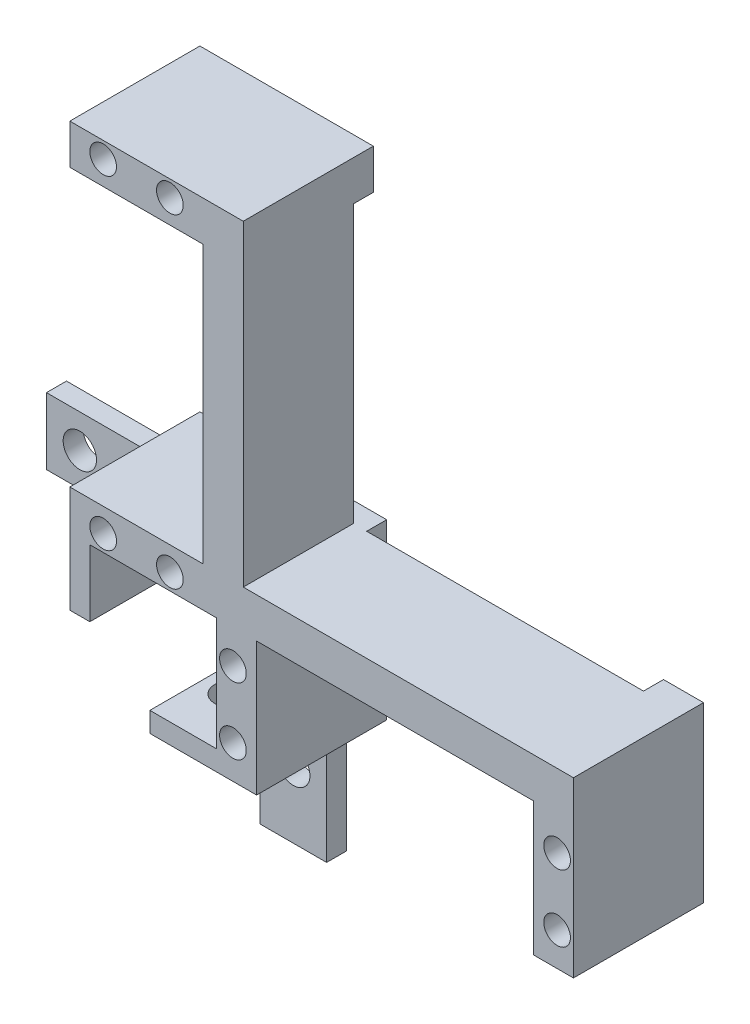
SolidWorks part; units mm, degrees
ref_plane "前视基准面" through (0, 0, 0) normal (0, 0, 1) x (1, 0, 0)
ref_plane "上视基准面" through (0, 0, 0) normal (0, 1, 0) x (1, 0, 0)
ref_plane "右视基准面" through (0, 0, 0) normal (1, 0, 0) x (0, 0, -1)
sketch "草图1" plane through (0, 0, 0) normal (0, 0, 1) x (1, 0, 0)
  line L0 (0, 38.2514) -> (0, 0) construction
  line L1 (0, 0) -> (26.75, 0)
  line L2 (26.75, 0) -> (26.75, -20)
  line L3 (26.75, -20) -> (36.75, -20)
  line L4 (0, -6) -> (20.75, -6)
  line L5 (20.75, -6) -> (20.75, -26)
  line L6 (20.75, -26) -> (36.75, -26)
  line L7 (-36.75, -20) -> (-36.75, -26)
  line L8 (36.75, -20) -> (36.75, -26)
  line L9 (-20.75, -26) -> (-36.75, -26)
  line L10 (-20.75, -6) -> (-20.75, -26)
  line L11 (0, -6) -> (-20.75, -6)
  line L12 (-26.75, -20) -> (-36.75, -20)
  line L13 (-26.75, 0) -> (-26.75, -20)
  line L14 (0, 0) -> (-26.75, 0)
  dimension "D2" = 41.5
  dimension "D3" = 20
  dimension "D4" = 10
  dimension "D5" = 0
  dimension "D1" = 6
extrude "凸台-拉伸1" add sketch "草图1" along normal blind 16.5
sketch "草图2" plane through (0, -20, 0) normal (0, 1, 0) x (1, 0, 0)
  line L0 (36.75, -16.5) -> (26.75, -16.5) construction
  line L1 (36.75, -16.5) -> (36.75, 0) construction
  circle A0 centre (32.75, -8.25) radius 2.5
  dimension "D1" = 5
  dimension "D2" = 8.25
  dimension "D3" = 4
extrude "切除-拉伸1" cut sketch "草图2" against normal blind 16.5
sketch "草图3" plane through (0, -20, 0) normal (0, 1, 0) x (1, 0, 0)
  line L1 (36.75, 0) -> (26.75, 0)
  line L2 (36.75, 0) -> (36.75, -16.5)
  line L3 (36.75, -16.5) -> (26.75, -16.5)
  line L4 (26.75, 0) -> (26.75, -16.5)
extrude "切除-拉伸2" cut sketch "草图3" against normal blind 3
sketch "草图4" plane through (0, 0, 16.5) normal (0, 0, 1) x (1, 0, 0)
  line L2 (-26.75, 0) -> (-38.6463, 0)
  line L3 (-26.75, 0) -> (-26.75, -29.0846)
  line L4 (-26.75, -29.0846) -> (-38.6463, -29.0846)
  line L5 (-38.6463, 0) -> (-38.6463, -29.0846)
extrude "切除-拉伸3" cut sketch "草图4" against normal through all
sketch "草图5" plane through (0, 0, 0) normal (0, 0, -1) x (-1, 0, 0)
  line L0 (20.75, -16) -> (-20.75, -16) construction
  line L1 (20.75, -26) -> (20.75, -6) construction
  line L2 (-20.75, -6) -> (-20.75, -26) construction
  line L3 (0, 0) -> (0, -37.9358) construction
  line L4 (-26.75, 0) -> (26.75, 0) construction
  circle A0 centre (-24.3, -11) radius 2
  circle A1 centre (-24.3, -21) radius 2
  circle A2 centre (24.3, -21) radius 2
  circle A3 centre (24.3, -11) radius 2
  dimension "D1" = 4
  dimension "D2" = 4
  dimension "D3" = 10
  dimension "D4" = 5
  dimension "D5" = 24.3
  dimension "D6" = 24.3
extrude "切除-拉伸4" cut sketch "草图5" against normal through all
sketch "草图6" plane through (0, 0, 0) normal (0, 0, -1) x (-1, 0, 0)
  line L1 (-26.75, -23) -> (-36.75, -23)
  line L2 (-26.75, -23) -> (-26.75, -46)
  line L3 (-26.75, -46) -> (-36.75, -46)
  line L4 (-36.75, -23) -> (-36.75, -46)
  dimension "D1" = 23
extrude "凸台-拉伸2" add sketch "草图6" along normal blind 3
sketch "草图7" plane through (0, 0, -3) normal (0, 0, -1) x (-1, 0, 0)
  line L0 (-36.75, -46) -> (-26.75, -46) construction
  line L1 (-36.75, -23) -> (-36.75, -46) construction
  circle A0 centre (-31.75, -36) radius 2.5
  dimension "D1" = 5
  dimension "D2" = 10
  dimension "D3" = 5
extrude "切除-拉伸5" cut sketch "草图7" against normal blind 3
sketch "草图8" plane through (0, 0, 0) normal (0, 0, -1) x (-1, 0, 0)
  line L0 (-36.75, -46) -> (-26.75, -46) construction
  line L1 (26.75, 0) -> (20.75, 0)
  line L2 (26.75, 0) -> (26.75, -26)
  line L3 (26.75, -46) -> (20.75, -46)
  line L4 (20.75, 0) -> (20.75, -46)
  line L6 (26.75, -46) -> (30.75, -46)
  line L8 (26.75, -26) -> (30.75, -26)
  line L9 (30.75, -46) -> (30.75, -26)
  line L11 (-20.75, -26) -> (-26.75, -26)
  line L12 (-20.75, -26) -> (-20.75, 0)
  line L13 (-20.75, 0) -> (-26.75, 0)
  line L14 (-26.75, -26) -> (-26.75, 0)
  circle A0 centre (24.3, -21) radius 2 construction
  circle A1 centre (24.3, -21) radius 2
  circle A2 centre (24.3, -11) radius 2 construction
  circle A3 centre (24.3, -11) radius 2
  circle A4 centre (-24.3, -11) radius 2 construction
  circle A5 centre (-24.3, -21) radius 2 construction
  circle A6 centre (-24.3, -11) radius 2
  circle A7 centre (-24.3, -21) radius 2
  dimension "D1" = 6
  dimension "D2" = 20
  dimension "D3" = 10
extrude "凸台-拉伸3" add sketch "草图8" along normal blind 3
sketch "草图9" plane through (0, 0, -3) normal (0, 0, -1) x (-1, 0, 0)
  line L0 (30.75, -46) -> (30.75, -26) construction
  line L1 (20.75, -46) -> (30.75, -46) construction
  circle A0 centre (25.75, -36) radius 2.5
  dimension "D1" = 5
  dimension "D2" = 5
  dimension "D3" = 10
extrude "切除-拉伸6" cut sketch "草图9" against normal blind 3
mirror "镜向1" about plane through (36.75, -20, 16.5) normal (-1, 0, 0) of bodies 114
sketch "草图10" plane through (0, 0, -3) normal (0, 0, -1) x (-1, 0, 0)
  line L0 (-46.75, -46) -> (-26.75, -46) construction
  line L1 (-36.75, -46) -> (37.944, -46)
  line L2 (-36.75, -46) -> (-36.75, 6.0951)
  line L3 (-36.75, 6.0951) -> (37.944, 6.0951)
  line L4 (37.944, -46) -> (37.944, 6.0951)
extrude "切除-拉伸7" cut sketch "草图10" against normal through all
sketch "草图11" plane through (0, 0, -3) normal (0, 0, -1) x (-1, 0, 0)
  line L1 (-94.25, -26) -> (-110.7326, -26)
  line L2 (-94.25, -26) -> (-94.25, -51.8105)
  line L3 (-94.25, -51.8105) -> (-110.7326, -51.8105)
  line L4 (-110.7326, -26) -> (-110.7326, -51.8105)
extrude "切除-拉伸8" cut sketch "草图11" against normal blind 10 contours L3 L4 L1 L2
ref_plane "基准面1" through (23.375, -23.375, 0) normal (-0.7071, 0.7071, 0) x (0, 0, -1)
sketch "草图13" plane through (0, 0, -3) normal (0, 0, -1) x (-1, 0, 0)
  line L1 (-24.75, -6) -> (-50.75, -6)
  line L2 (-24.75, -6) -> (-24.75, 0)
  line L3 (-24.75, 47.5) -> (-50.75, 47.5)
  line L4 (-50.75, -6) -> (-50.75, 47.5)
  line L6 (-36.75, -23) -> (-46.75, -23) construction
  line L9 (-46.75, 0) -> (-46.75, -23) construction
  line L11 (-24.75, 41.5) -> (-44.75, 41.5)
  line L12 (-44.75, 20.75) -> (-8.0679, 20.75) construction
  line L13 (-24.75, 0) -> (-44.75, 0)
  line L14 (-44.75, 41.5) -> (-44.75, 0)
  line L16 (-24.75, 41.5) -> (-24.75, 47.5)
  line L17 (-34.75, 41.5) -> (-34.75, 0) construction
  circle A1 centre (-29.75, -3.55) radius 2
  circle A2 centre (-39.75, -3.55) radius 2
  circle A6 centre (-39.75, 45.05) radius 2
  circle A7 centre (-29.75, 45.05) radius 2
  dimension "D8" = 4
  dimension "D9" = 4
  dimension "D10" = 10
  dimension "D11" = 48.6
  dimension "D12" = 5
  dimension "D13" = 5
  dimension "D1" = 26
  dimension "D2" = 17
  dimension "D3" = 53.5
  dimension "D4" = 4
  dimension "D5" = 20
  dimension "D6" = 41.5
  dimension "D7" = 6
extrude "凸台-拉伸4" add sketch "草图13" against normal up to surface (19.5 mm away) up to face at (66.15, -16.2, 16.5)
sketch "草图14" plane through (0, 0, -3) normal (0, 0, -1) x (-1, 0, 0)
  line L0 (-44.75, 0) -> (-44.75, 41.5) construction
  line L1 (-44.75, 41.5) -> (-50.75, 41.5)
  line L2 (-44.75, 41.5) -> (-44.75, 0)
  line L3 (-44.75, 0) -> (-50.75, 0)
  line L4 (-50.75, 41.5) -> (-50.75, 0)
  line L7 (-24.75, 41.5) -> (-24.75, 0) construction
  line L8 (-24.75, 20.75) -> (-33.9969, 20.75) construction
  dimension "D1" = 41.5
  dimension "D2" = 6
  dimension "D3" = 20.75
extrude "切除-拉伸9" cut sketch "草图14" against normal up to surface (3 mm away) up to face at (73.5, -3, 0)
sketch "草图15" plane through (0, 0, -3) normal (0, 0, -1) x (-1, 0, 0)
  line L1 (-4.75, -6) -> (-27.75, -6)
  line L2 (-4.75, -6) -> (-4.75, -16)
  line L3 (-4.75, -16) -> (-27.75, -16)
  line L4 (-27.75, -6) -> (-27.75, -16)
  line L6 (-24.75, -6) -> (-24.75, 0) construction
  line L9 (-46.75, -6) -> (-24.75, -6) construction
  circle A0 centre (-9.75, -11) radius 2.5
  dimension "D5" = 5
  dimension "D6" = 5
  dimension "D7" = 5
  dimension "D1" = 3
  dimension "D2" = 10
  dimension "D3" = 23
  dimension "D4" = 0
extrude "凸台-拉伸5" add sketch "草图15" against normal blind 3
sketch "草图16" plane through (0, 0, 0) normal (0, 0, 1) x (1, 0, 0)
  line L0 (24.75, -6) -> (27.75, -6) construction
  line L1 (27.75, -16) -> (24.75, -16)
  line L2 (27.75, -16) -> (27.75, -6)
  line L3 (27.75, -6) -> (24.75, -6)
  line L4 (24.75, -16) -> (24.75, -6)
  line L5 (4.75, -6) -> (24.75, -6) construction
extrude "凸台-拉伸6" add sketch "草图16" along normal up to surface (16.5 mm away) up to face at (52.8611, 0.2222, 16.5)
sketch "草图17" plane through (24.75, 0, 0) normal (-1, 0, 0) x (0, 0, 1)
  line L3 (16.5, -16) -> (16.5, 0) construction
  line L4 (16.5, -16) -> (0, -16) construction
  circle A0 centre (6.5, -11) radius 2.5
  dimension "D1" = 10
  dimension "D2" = 5
  dimension "D3" = 5
extrude "切除-拉伸10" cut sketch "草图17" against normal blind 3
